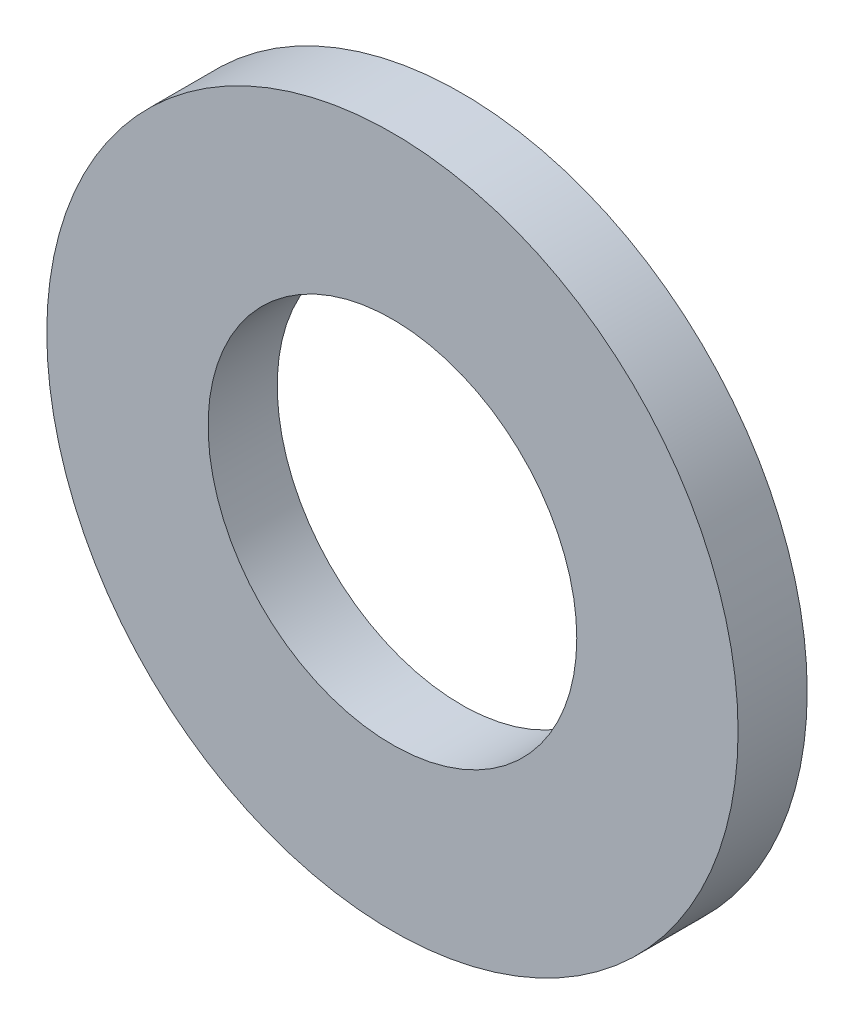
SolidWorks part; units mm, degrees
material "AISI 304"
ref_plane "Front Plane" through (0, 0, 0) normal (0, 0, 1) x (1, 0, 0)
ref_plane "Top Plane" through (0, 0, 0) normal (0, 1, 0) x (1, 0, 0)
ref_plane "Right Plane" through (0, 0, 0) normal (1, 0, 0) x (0, 0, -1)
sketch "Sketch1" plane through (0, 0, 0) normal (0, 0, 1) x (1, 0, 0)
  circle A0 centre (0, 0) radius 3
  circle A1 centre (0, 0) radius 1.6
  dimension "D1" = 3.2
  dimension "D2" = 6
extrude "Boss-Extrude1" add sketch "Sketch1" along normal blind 0.6
equation "\"ID\"=0.0032"
equation "\"OD\"=0.006"
equation "\"H\"=0.0006"
equation "\"D1@Sketch1\"=\"ID\"*1000"
equation "\"D2@Sketch1\"=\"OD\"*1000"
equation "\"D1@Boss-Extrude1\"=\"H\"*1000"
